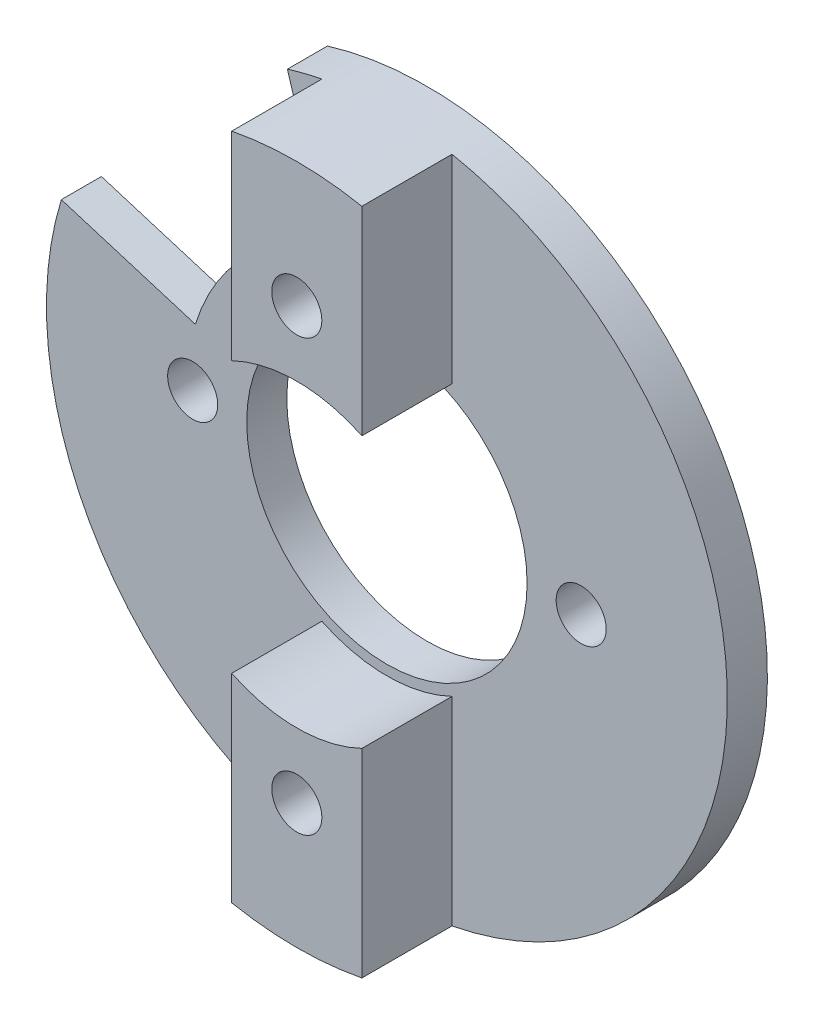
SolidWorks part; units mm, degrees
ref_plane "前视基准面" through (0, 0, 0) normal (0, 0, 1) x (1, 0, 0)
ref_plane "上视基准面" through (0, 0, 0) normal (0, 1, 0) x (1, 0, 0)
ref_plane "右视基准面" through (0, 0, 0) normal (1, 0, 0) x (0, 0, -1)
sketch "草图1" plane through (0, 0, 0) normal (0, 0, 1) x (1, 0, 0)
  circle A0 centre (0, 0) radius 17
  circle A1 centre (0, 0) radius 10 construction
  circle A2 centre (0, 0) radius 6.5 construction
  dimension "D1" = 34
  dimension "D2" = 20
  dimension "D3" = 13
extrude "凸台-拉伸1" add sketch "草图1" along normal blind 2
sketch "草图2" plane through (0, 0, 0) normal (0, 0, -1) x (-1, 0, 0)
  line L0 (9.75, 0) -> (-9.75, 0) construction
  circle A0 centre (0, 0) radius 7
  circle A6 centre (0, 0) radius 9.75 construction
  circle A7 centre (-9.75, 0) radius 1.25
  circle A8 centre (9.75, 0) radius 1.25
  point P15 (0.25, 0.25)
  dimension "D1" = 14
  dimension "D2" = 19.5
  dimension "D3" = 2.5
  dimension "D4" = 2.5
extrude "切除-拉伸1" cut sketch "草图2" against normal blind 2
sketch "草图11" plane through (0, 0, 0) normal (0, 0, -1) x (-1, 0, 0)
  line L0 (0, 0) -> (4.9703, 16.2572) construction
  line L1 (0, 10) -> (10, 0) construction
  line L2 (0, 0) -> (12.0208, 12.0208) construction
  line L3 (0, 0) -> (16.2572, 4.9703) construction
  line L4 (4.9703, 16.2572) -> (2.9237, 9.563)
  line L5 (16.2572, 4.9703) -> (9.563, 2.9237)
  circle A0 centre (0, 0) radius 10 construction
  circle A1 centre (0, 0) radius 17 construction
  arc A2 (2.9237, 9.563) -> (9.563, 2.9237) centre (0, 0) cw
  arc A3 (4.9703, 16.2572) -> (16.2572, 4.9703) centre (0, 0) cw
  point P10 (2.9237, 9.563)
  point P11 (9.563, 2.9237)
  circle M10 centre (0, 0) radius 17
  dimension "D1" = 20
  dimension "D2" = 28
sketch "草图13" plane through (0, 0, 2) normal (0, 0, 1) x (1, 0, 0)
  line L0 (0, 17) -> (0, -17) construction
  line L1 (3.5, 16.6358) -> (3.5, -16.6358) construction
  line L2 (3.5, 13.5554) -> (3.5, 16.6358)
  line L3 (-3.5, 13.5554) -> (-3.5, 16.6358)
  line L4 (-3.5, -13.5554) -> (-3.5, -16.6358)
  line L5 (3.5, -13.5554) -> (3.5, -16.6358)
  circle A0 centre (0, 0) radius 14 construction
  circle A1 centre (0, 0) radius 17 construction
  circle A2 centre (0, 0) radius 17 construction
  arc A3 (-3.5, 13.5554) -> (3.5, 13.5554) centre (0, 0) ccw
  arc A4 (-3.5, 13.5554) -> (3.5, 13.5554) centre (0, 0) cw
  arc A5 (-3.5, 16.6358) -> (3.5, 16.6358) centre (0, 0) cw
  arc A6 (3.5, -13.5554) -> (-3.5, -13.5554) centre (0, 0) cw
  arc A7 (3.5, -16.6358) -> (-3.5, -16.6358) centre (0, 0) cw
  point P10 (3.5, 13.5554)
  point P21 (0, 0)
  dimension "D1" = 28
  dimension "D4" = 34
  dimension "D2" = 3.5
  dimension "D3" = 2
extrude "切除-拉伸3" cut sketch "草图11" against normal blind 2.5 contours L4 A2 L5 M10
sketch "草图24" plane through (0, 0, 2) normal (0, 0, 1) x (1, 0, 0)
  line L0 (0, 17) -> (0, -17) construction
  line L1 (3.25, 16.6864) -> (3.25, 6.7593)
  line L2 (-3.25, 16.6864) -> (-3.25, 6.7593)
  line L3 (3.25, -16.6864) -> (3.25, -6.7593)
  line L4 (-3.25, -16.6864) -> (-3.25, -6.7593)
  arc A0 (-16.2572, 4.9703) -> (-4.9703, 16.2572) centre (0, 0) ccw construction
  circle A1 centre (0, 0) radius 7.5 construction
  arc A2 (-3.25, 16.6864) -> (3.25, 16.6864) centre (0, 0) cw
  arc A3 (-3.25, 6.7593) -> (3.25, 6.7593) centre (0, 0) cw
  arc A4 (3.25, -16.6864) -> (-3.25, -16.6864) centre (0, 0) cw
  arc A5 (3.25, -6.7593) -> (-3.25, -6.7593) centre (0, 0) cw
  point P20 (0, 0)
  dimension "D1" = 15
  dimension "D3" = 2
  dimension "D2" = 3.25
extrude "凸台-拉伸6" add sketch "草图24" along normal blind 4.5
sketch "草图25" plane through (0, 0, 6.5) normal (0, 0, 1) x (1, 0, 0)
  line L0 (17, 0) -> (-17, 0) construction
  circle A0 centre (0, 0) radius 10.75 construction
  circle A1 centre (0, 10.75) radius 1.25
  arc A2 (3.25, -16.6864) -> (3.25, 16.6864) centre (0, 0) ccw construction
  arc A3 (-16.2572, 4.9703) -> (-3.25, -16.6864) centre (0, 0) ccw construction
  circle A4 centre (0, -10.75) radius 1.25
  dimension "D1" = 21.5
  dimension "D2" = 2.5
extrude "切除-拉伸4" cut sketch "草图25" against normal blind 4
sketch "草图27" plane through (0, 0, 0) normal (0, 0, -1) x (-1, 0, 0)
  line L0 (-9.7, 0) -> (9.7, 0) construction
  circle A0 centre (0, 0) radius 9.7 construction
  circle A1 centre (-9.7, 0) radius 1.25
  circle A2 centre (9.7, 0) radius 1.25
  dimension "D1" = 19.4
  dimension "D2" = 2.5
  dimension "D3" = 2.5
extrude "切除-拉伸5" cut sketch "草图27" against normal blind 2 contours A1 | A2
